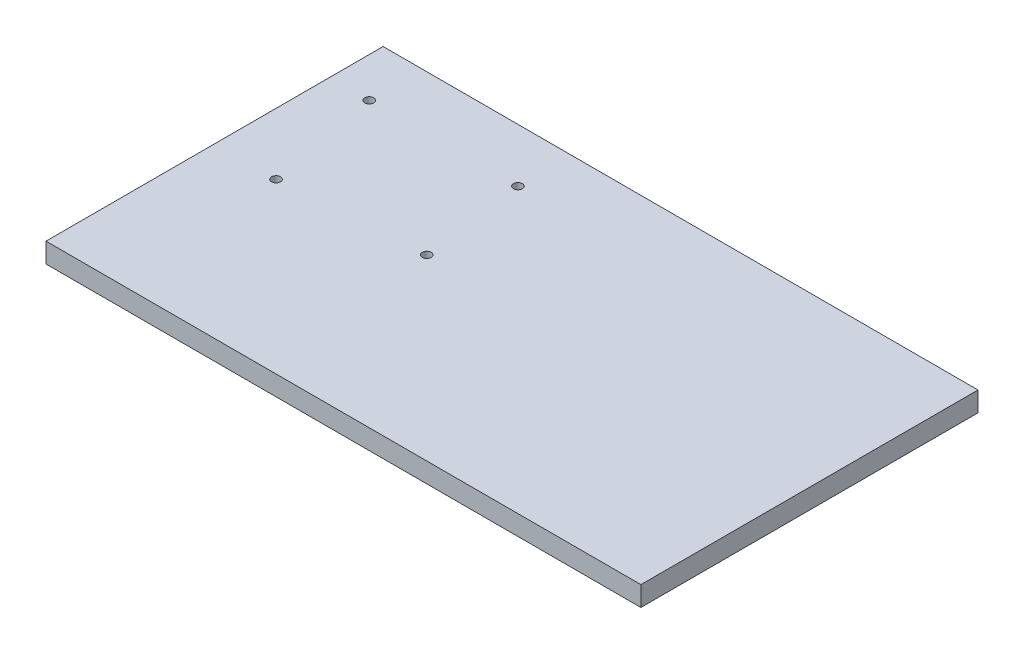
SolidWorks part; units mm, degrees
ref_plane "Спереди" through (0, 0, 0) normal (0, 0, 1) x (1, 0, 0)
ref_plane "Сверху" through (0, 0, 0) normal (0, 1, 0) x (1, 0, 0)
ref_plane "Справа" through (0, 0, 0) normal (1, 0, 0) x (0, 0, -1)
sketch "Эскиз1" plane through (0, 0, 0) normal (0, 1, 0) x (1, 0, 0)
  line L0 (20, 143) -> (95, 143) construction
  line L1 (95, 143) -> (95, 90) construction
  line L2 (95, 90) -> (20, 90) construction
  line L3 (20, 90) -> (20, 143) construction
  line L5 (31, 84.9978) -> (31, 90) construction
  line L6 (95, 90) -> (102, 90) construction
  line L35 (0, 170) -> (300, 170)
  line L36 (0, 170) -> (0, 0)
  line L37 (0, 0) -> (300, 0)
  line L38 (300, 170) -> (300, 0)
  circle A0 centre (20, 143) radius 2.25
  circle A1 centre (95, 143) radius 2.25
  circle A2 centre (102, 90) radius 2.25
  circle A3 centre (31, 84.9978) radius 2.25
  dimension "D7" = 20
  dimension "D8" = 90
  dimension "D9" = 300
  dimension "D1" = 7
  dimension "D2" = 75
  dimension "D4" = 5.0022
  dimension "D5" = 53
  dimension "D6" = 11
  dimension "D32" = 170
extrude "Бобышка-Вытянуть1" add sketch "Эскиз1" along normal blind 10
